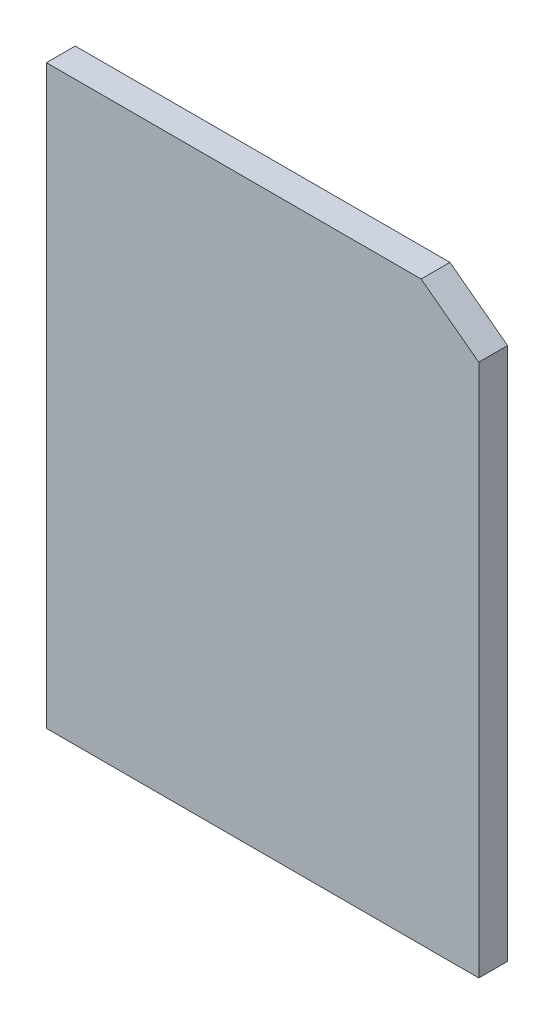
SolidWorks part; units mm, degrees
ref_plane "前视基准面" through (0, 0, 0) normal (0, 0, 1) x (1, 0, 0)
ref_plane "上视基准面" through (0, 0, 0) normal (0, 1, 0) x (1, 0, 0)
ref_plane "右视基准面" through (0, 0, 0) normal (1, 0, 0) x (0, 0, -1)
other "Configuration Table"
sketch "草图1" plane through (0, 0, 0) normal (0, 0, 1) x (1, 0, 0)
  line L2 (-3.6807, 2.0521) -> (-3.6807, -5.9479)
  line L3 (-3.6807, -5.9479) -> (2.3193, -5.9479)
  line L6 (2.3193, 1.4521) -> (1.5193, 2.0521)
  line L7 (-3.6807, 2.0521) -> (1.5193, 2.0521)
  line L8 (2.3193, 1.4521) -> (2.3193, -5.9479)
  dimension "D2" = 8
extrude "凸台-拉伸1" add sketch "草图1" along normal blind 0.4
